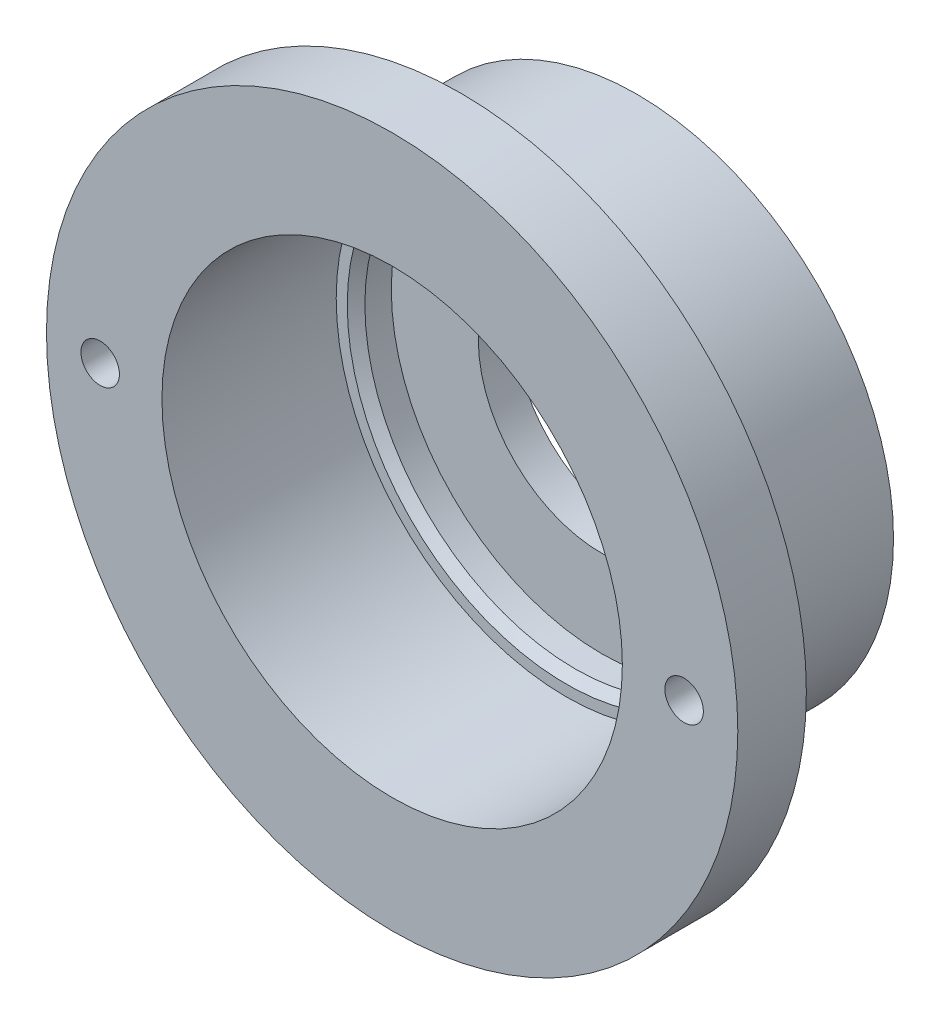
SolidWorks part; units mm, degrees
ref_plane "Front Plane" through (0, 0, 0) normal (0, 0, 1) x (1, 0, 0)
ref_plane "Top Plane" through (0, 0, 0) normal (0, 1, 0) x (1, 0, 0)
ref_plane "Right Plane" through (0, 0, 0) normal (1, 0, 0) x (0, 0, -1)
sketch "Sketch1" plane through (0, 0, 0) normal (0, 1, 0) x (1, 0, 0)
  line L0 (0, 25.4113) -> (0, -24.5124) construction
  line L2 (-7, 4.7005) -> (-19.6178, 4.7005)
  line L3 (-7, 4.7005) -> (-7, 2.7005)
  line L4 (-7, 2.7005) -> (-19.6178, 2.7005)
  line L5 (-19.6178, 4.7005) -> (-19.6178, 2.7005)
  line L6 (-11.938, 2.7005) -> (-19.6178, 2.7005)
  line L7 (-11.938, 2.7005) -> (-11.938, 0.7005)
  line L8 (-11.938, 0.7005) -> (-19.6178, 0.7005)
  line L9 (-19.6178, 2.7005) -> (-19.6178, 0.7005)
  line L10 (-13.0646, 0.7005) -> (-19.6178, 0.7005)
  line L11 (-13.0646, 0.7005) -> (-13.0646, -9.1895)
  line L12 (-13.0646, -9.1895) -> (-19.6178, -9.1895)
  line L13 (-19.6178, 0.7005) -> (-19.6178, -9.1895)
  dimension "D1" = 7
  dimension "D2" = 2
  dimension "D3" = 2
  dimension "D4" = 13.89
  dimension "D5" = 11.938
  dimension "D6" = 6.5532
revolve "Revolve1" add sketch "Sketch1" angle 360 about L0
sketch "Sketch2" plane through (0, 0, -4.7005) normal (0, 0, -1) x (-1, 0, 0)
  line L0 (19.6178, 0) -> (-19.6178, 0) construction
  line L1 (0, 19.4384) -> (0, -19.6178) construction
  circle A0 centre (0, 0) radius 19.6178 construction
  circle A1 centre (0, 0) radius 14.565
  circle A2 centre (0, 0) radius 26.6528
  dimension "D1" = 29.13
extrude "Cut-Extrude1" cut sketch "Sketch2" against normal blind 10
sketch "Sketch4" plane through (0, 0, 5.2995) normal (0, 0, -1) x (-1, 0, 0)
  line L0 (19.6178, 0) -> (-19.6178, 0) construction
  line L1 (0, 18.9883) -> (0, -18.5199) construction
  circle A0 centre (0, 0) radius 19.6178 construction
  circle A1 centre (16.57, 0) radius 1.0922
  circle A2 centre (0, 0) radius 14.565 construction
  circle A3 centre (-16.57, 0) radius 1.0922
  point P11 (14.565, 0)
  point P15 (0, 0)
  dimension "D1" = 2.1844
  dimension "D2" = 16.57
extrude "Cut-Extrude2" cut sketch "Sketch4" against normal through all
chamfer "Chamfer1" distance 0.5 angle 45 1 edges at (-11.938, 0, -0.7005)
